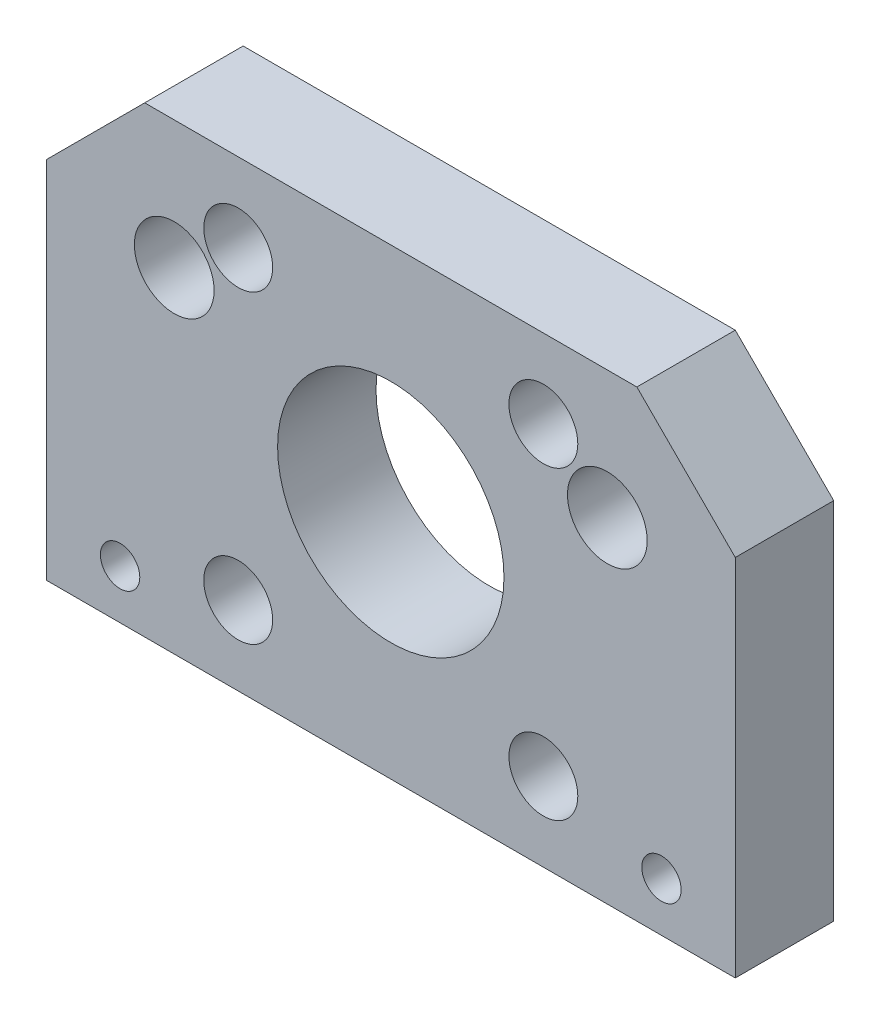
SolidWorks part; units mm, degrees
ref_plane "Front Plane" through (0, 0, 0) normal (0, 0, 1) x (1, 0, 0)
ref_plane "Top Plane" through (0, 0, 0) normal (0, 1, 0) x (1, 0, 0)
ref_plane "Right Plane" through (0, 0, 0) normal (1, 0, 0) x (0, 0, -1)
sketch "Sketch1" plane through (0, 0, 0) normal (0, 0, 1) x (1, 0, 0)
  line L1 (-35, 23.5) -> (35, 23.5)
  line L2 (-35, 23.5) -> (-35, -23.5)
  line L3 (-35, -23.5) -> (35, -23.5)
  line L4 (35, 23.5) -> (35, -23.5)
  line L5 (-35, 23.5) -> (35, -23.5) construction
  line L6 (-35, -23.5) -> (35, 23.5) construction
  point P0 (0, 0)
  dimension "D1" = 70
  dimension "D2" = 47
extrude "Boss-Extrude1" add sketch "Sketch1" along normal blind 10
sketch "Sketch2" plane through (0, 0, 10) normal (0, 0, 1) x (1, 0, 0)
  circle A0 centre (0, 0) radius 11.5
  dimension "D1" = 23
extrude "Cut-Extrude1" cut sketch "Sketch2" against normal blind 10
sketch "Sketch3" plane through (0, 0, 10) normal (0, 0, 1) x (1, 0, 0)
  circle A0 centre (-15.5, 15.5) radius 1.5
  circle A1 centre (15.5, 15.5) radius 1.5
  circle A2 centre (15.5, -15.5) radius 1.5
  circle A3 centre (-15.5, -15.5) radius 1.5
  dimension "D1" = 3
  dimension "D2" = 3
  dimension "D3" = 3
  dimension "D4" = 3
  dimension "D5" = 31
  dimension "D6" = 31
  dimension "D7" = 31
  dimension "D8" = 31
  dimension "D9" = 15.5
  dimension "D10" = 15.5
  dimension "D11" = 15.5
  dimension "D12" = 15.5
extrude "Cut-Extrude2" cut sketch "Sketch3" against normal blind 10
sketch "Sketch4" plane through (0, 0, 10) normal (0, 0, 1) x (1, 0, 0)
  line L0 (-35, 23.5) -> (-35, -23.5) construction
  line L1 (35, -23.5) -> (35, 23.5) construction
  line L2 (35, 23.5) -> (-35, 23.5) construction
  circle A0 centre (-22, 10.5) radius 4.05
  circle A1 centre (22, 10.5) radius 4.05
  dimension "D5" = 8.1
  dimension "D6" = 8.1
  dimension "D1" = 13
  dimension "D2" = 13
  dimension "D3" = 13
  dimension "D4" = 13
extrude "Cut-Extrude3" cut sketch "Sketch4" against normal blind 10
sketch "Sketch6" plane through (0, 0, 10) normal (0, 0, 1) x (1, 0, 0)
  line L0 (-35, 23.5) -> (-35, -23.5) construction
  line L1 (35, -23.5) -> (35, 23.5) construction
  line L2 (-35, -23.5) -> (35, -23.5) construction
  circle A0 centre (-27.5, -18.5) radius 2
  circle A2 centre (27.5, -18.5) radius 2
  dimension "D7" = 4
  dimension "D9" = 4
  dimension "D1" = 7.5
  dimension "D2" = 7.5
  dimension "D4" = 5
  dimension "D6" = 5
extrude "Cut-Extrude5" cut sketch "Sketch6" against normal blind 10
sketch "Sketch7" plane through (0, 0, 10) normal (0, 0, 1) x (1, 0, 0)
  circle A0 centre (-15.5, -15.5) radius 3.5
  circle A1 centre (-15.5, 15.5) radius 3.5
  circle A2 centre (15.5, 15.5) radius 3.5
  circle A3 centre (15.5, -15.5) radius 3.5
  dimension "D1" = 7
  dimension "D2" = 7
  dimension "D3" = 7
  dimension "D4" = 7
extrude "Cut-Extrude6" cut sketch "Sketch7" against normal blind 7
chamfer "Chamfer1" distance 10 angle 45 2 edges at (35, 23.5, 5) (-35, 23.5, 5)
sketch3d "Sketch_MAC1-1_NEMA 17 MOUNT" [suppressed]
  line L0 (-35, -22.5, 8) -> (-25, -22.5, 8)
  line L1 (-35, -22.5, 8) -> (-35, -12.5, 8)
  point P0 (-35, -22.5, 8)
  point P1 (-25, -22.5, 8)
  point P2 (-35, -12.5, 8)
sketch3d "Stock_NEMA 17 MOUNT"
  line L12 (-35, -22.5, 0) -> (35, -22.5, 0)
  line L13 (35, -22.5, 0) -> (35, 22.5, 0)
  line L14 (35, 22.5, 0) -> (-35, 22.5, 0)
  line L15 (-35, 22.5, 0) -> (-35, -22.5, 0)
  line L16 (-35, -22.5, 8) -> (35, -22.5, 8)
  line L17 (35, -22.5, 8) -> (35, 22.5, 8)
  line L18 (35, 22.5, 8) -> (-35, 22.5, 8)
  line L19 (-35, 22.5, 8) -> (-35, -22.5, 8)
  line L20 (-35, -22.5, 0) -> (-35, -22.5, 8)
  line L21 (35, -22.5, 0) -> (35, -22.5, 8)
  line L22 (35, 22.5, 0) -> (35, 22.5, 8)
  line L23 (-35, 22.5, 0) -> (-35, 22.5, 8)
  point P35 (0, -22.5, 0)
  point P36 (35, 0, 0)
  point P37 (0, 22.5, 0)
  point P38 (-35, 0, 0)
  point P39 (0, -22.5, 8)
  point P40 (35, 0, 8)
  point P41 (0, 22.5, 8)
  point P42 (-35, 0, 8)
  point P43 (-35, -22.5, 4)
  point P44 (35, -22.5, 4)
  point P45 (35, 22.5, 4)
  point P46 (-35, 22.5, 4)
  point P47 (0, 0, 4)
  point P48 (0, -22.5, 4)
  point P49 (0, 0, 8)
  point P50 (0, 22.5, 4)
  point P51 (0, 0, 0)
  point P52 (-35, 0, 4)
  point P53 (35, 0, 4)
